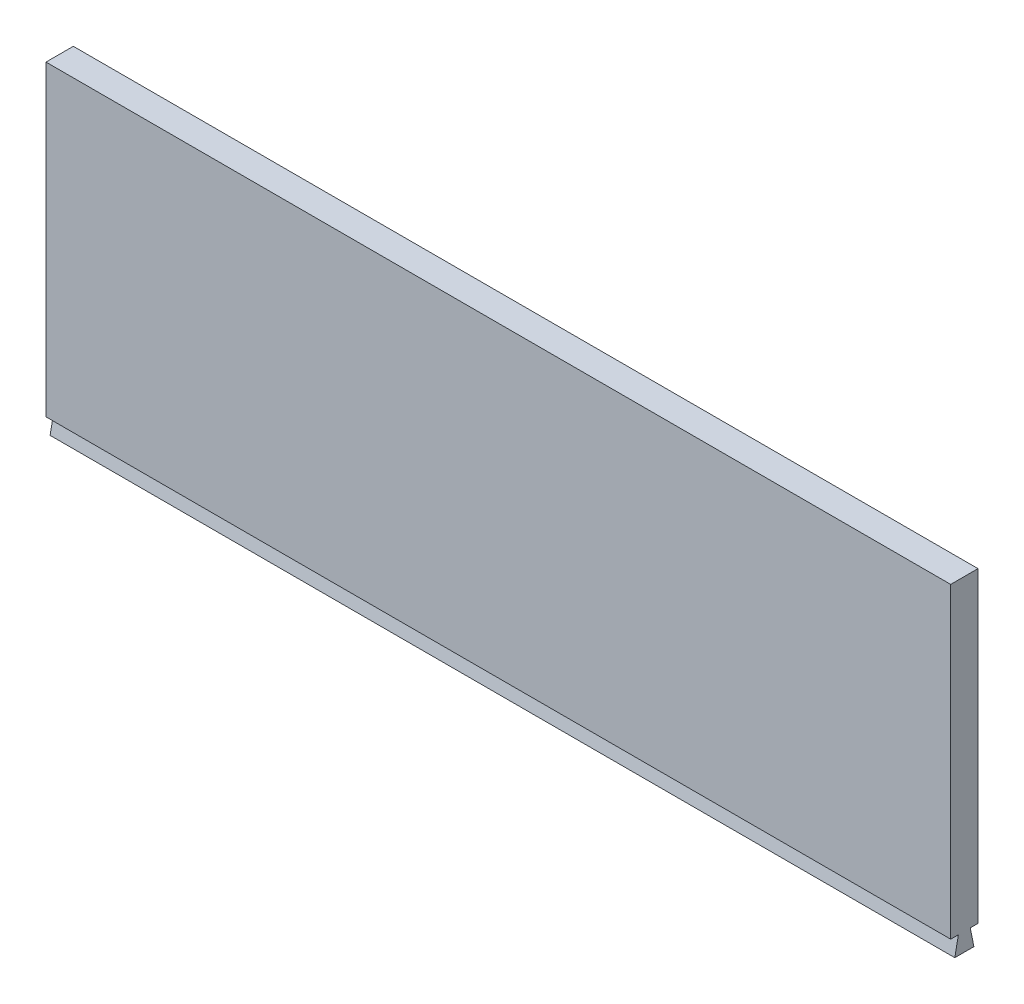
SolidWorks part; units mm, degrees
ref_plane "Front Plane" through (0, 0, 0) normal (0, 0, 1) x (1, 0, 0)
ref_plane "Top Plane" through (0, 0, 0) normal (0, 1, 0) x (1, 0, 0)
ref_plane "Right Plane" through (0, 0, 0) normal (1, 0, 0) x (0, 0, -1)
sketch "Sketch1" plane through (0, 0, 0) normal (0, 0, 1) x (1, 0, 0)
  line L1 (0, 0) -> (265, 0)
  line L2 (0, 0) -> (0, 90)
  line L3 (0, 90) -> (265, 90)
  line L4 (265, 0) -> (265, 90)
  dimension "D1" = 265
  dimension "D2" = 90
extrude "Boss-Extrude1" add sketch "Sketch1" along normal blind 8
sketch "Sketch3" plane through (0, 0, 0) normal (-1, 0, 0) x (0, 0, 1)
  line L0 (2.26, 0) -> (1.2, -5.3)
  line L1 (8, 0) -> (0, 0) construction
  line L2 (1.2, -5.3) -> (6.8, -5.3)
  line L3 (6.8, -5.3) -> (5.74, 0)
  line L4 (0, 90) -> (0, 0) construction
  line L5 (8, 90) -> (8, 0) construction
  line L6 (2.26, 0) -> (5.74, 0)
  line L7 (8, 0) -> (8, 90) construction
  line L8 (4, 0) -> (4, -5) construction
  line L9 (0, 0) -> (0, 90) construction
  point P4 (4, 0)
  dimension "D1" = 5.3
  dimension "D2" = 2.8
  dimension "D3" = 2.26
  dimension "D4" = 2.26
  dimension "D5" = 2.8
  dimension "D6" = 1.2
  dimension "D7" = 4
  dimension "D8" = 3.48
  dimension "D9" = 5.6
  dimension "D10" = 1.2
  dimension "D11" = 3.48
extrude "Boss-Extrude3" add sketch "Sketch3" against normal through all
